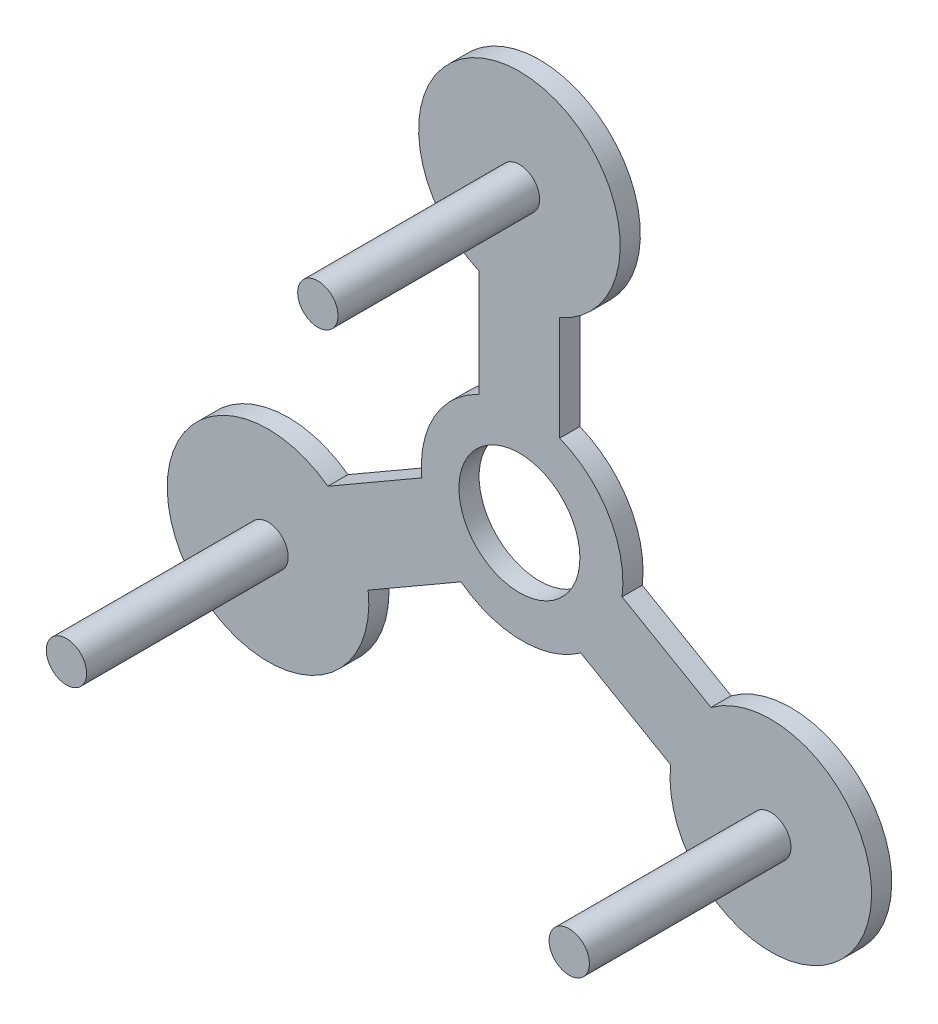
SolidWorks part; units mm, degrees
ref_plane "Front Plane" through (0, 0, 0) normal (0, 0, 1) x (1, 0, 0)
ref_plane "Top Plane" through (0, 0, 0) normal (0, 1, 0) x (1, 0, 0)
ref_plane "Right Plane" through (0, 0, 0) normal (1, 0, 0) x (0, 0, -1)
sketch "Sketch1" plane through (0, 0, 0) normal (0, 0, 1) x (1, 0, 0)
  line L0 (0, 0) -> (0, 144) construction
  line L1 (20, 144) -> (-20, 144)
  line L6 (0, 0) -> (124.7077, -72) construction
  line L7 (0, 0) -> (-124.7077, -72) construction
  line L8 (114.7077, -89.3205) -> (134.7077, -54.6795)
  line L9 (-114.7077, -89.3205) -> (-134.7077, -54.6795)
  line L10 (-134.7077, -54.6795) -> (-20, 11.547)
  line L11 (-20, 11.547) -> (-20, 144)
  line L12 (20, 144) -> (20, 11.547)
  line L13 (20, 11.547) -> (134.7077, -54.6795)
  line L14 (114.7077, -89.3205) -> (0, -23.094)
  line L15 (0, -23.094) -> (-114.7077, -89.3205)
  point P6 (0, 144)
  point P10 (0, 0)
  point P12 (124.7077, -72)
  point P15 (-124.7077, -72)
  dimension "D1" = 3
extrude "Boss-Extrude2" add sketch "Sketch1" along normal blind 10
sketch "Sketch3" plane through (0, 0, 10) normal (0, 0, 1) x (1, 0, 0)
  line L0 (-134.7077, -54.6795) -> (-114.7077, -89.3205) construction
  circle A0 centre (-124.7077, -72) radius 50
  circle A1 centre (0, 144) radius 50
  circle A2 centre (124.7077, -72) radius 50
  point P11 (0, 0)
  dimension "D1" = 3
extrude "Boss-Extrude3" add sketch "Sketch3" against normal blind 10
sketch "Sketch4" plane through (0, 0, 10) normal (0, 0, 1) x (1, 0, 0)
  circle A1 centre (0, 144) radius 10
  circle A2 centre (124.7077, -72) radius 10
  circle A3 centre (-124.7077, -72) radius 10
  point P9 (0, 0)
  dimension "D1" = 3
extrude "Boss-Extrude4" add sketch "Sketch4" along normal blind 90
sketch "Sketch5" plane through (0, 0, 100) normal (0, 0, 1) x (1, 0, 0)
  circle A0 centre (0, 144) radius 10
extrude "Cut-Extrude1" cut sketch "Sketch5" against normal blind 30
sketch "Sketch6" plane through (0, 0, 10) normal (0, 0, 1) x (1, 0, 0)
  circle A0 centre (0, 0) radius 13
extrude "Cut-Extrude2" cut sketch "Sketch6" against normal blind 10
sketch "Sketch7" plane through (0, 0, 70) normal (0, 0, 1) x (1, 0, 0)
  circle A0 centre (0, 144) radius 10
extrude "Boss-Extrude5" add sketch "Sketch7" along normal blind 30
sketch "Sketch9" plane through (0, 0, 100) normal (0, 0, 1) x (1, 0, 0)
  circle A0 centre (0, 144) radius 10
extrude "Boss-Extrude6" add sketch "Sketch9" along normal blind 10
sketch "Sketch10" plane through (0, 0, 100) normal (0, 0, 1) x (1, 0, 0)
  circle A0 centre (-124.7077, -72) radius 10
extrude "Boss-Extrude7" add sketch "Sketch10" along normal blind 10
sketch "Sketch11" plane through (0, 0, 100) normal (0, 0, 1) x (1, 0, 0)
  circle A0 centre (124.7077, -72) radius 10
extrude "Boss-Extrude8" add sketch "Sketch11" along normal blind 10
sketch "Sketch12" plane through (0, 0, 10) normal (0, 0, 1) x (1, 0, 0)
  circle A0 centre (1.3308, 0) radius 50
extrude "Boss-Extrude9" add sketch "Sketch12" against normal blind 10
sketch "Sketch13" plane through (0, 0, 10) normal (0, 0, 1) x (1, 0, 0)
  circle A0 centre (0, 0) radius 30
extrude "Cut-Extrude3" cut sketch "Sketch13" against normal blind 10
scale "Scale1" bodies to scale 112 scale about centroid uniform scaling yes scale factor 0.2
